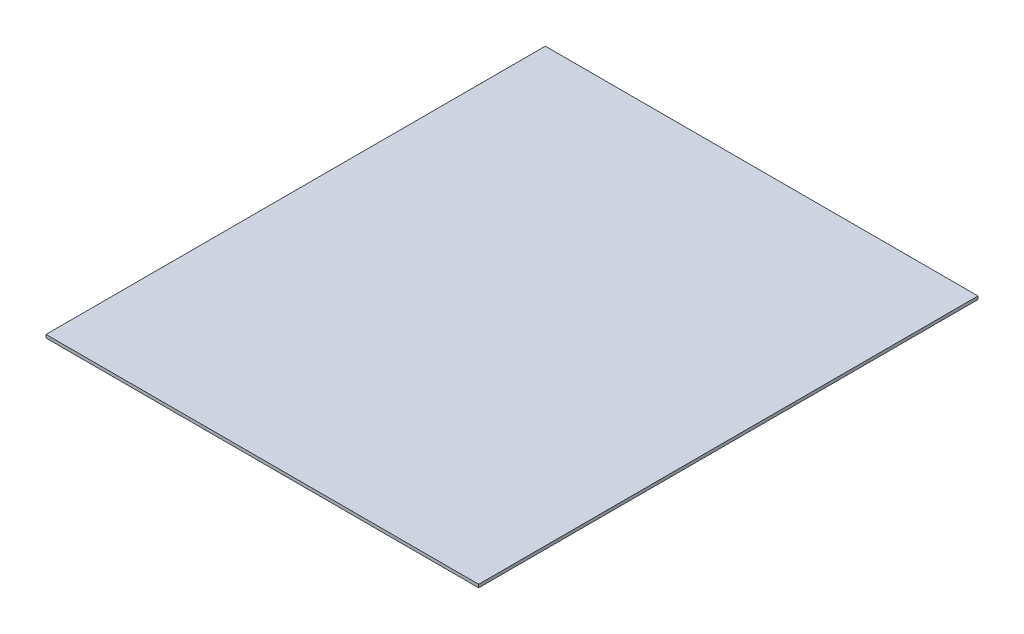
SolidWorks part; units mm, degrees
ref_plane "Front Plane" through (0, 0, 0) normal (0, 0, 1) x (1, 0, 0)
ref_plane "Top Plane" through (0, 0, 0) normal (0, 1, 0) x (1, 0, 0)
ref_plane "Right Plane" through (0, 0, 0) normal (1, 0, 0) x (0, 0, -1)
sketch "Sketch1" plane through (0, 0, 0) normal (0, 1, 0) x (1, 0, 0)
  line L1 (-138.65, 160) -> (138.65, 160)
  line L2 (-138.65, 160) -> (-138.65, -160)
  line L3 (-138.65, -160) -> (138.65, -160)
  line L4 (138.65, 160) -> (138.65, -160)
  line L5 (-138.65, 160) -> (138.65, -160) construction
  line L6 (-138.65, -160) -> (138.65, 160) construction
  point P0 (0, 0)
  dimension "D1" = 277.3
  dimension "D2" = 320
extrude "Base" add sketch "Sketch1" along normal blind 2
